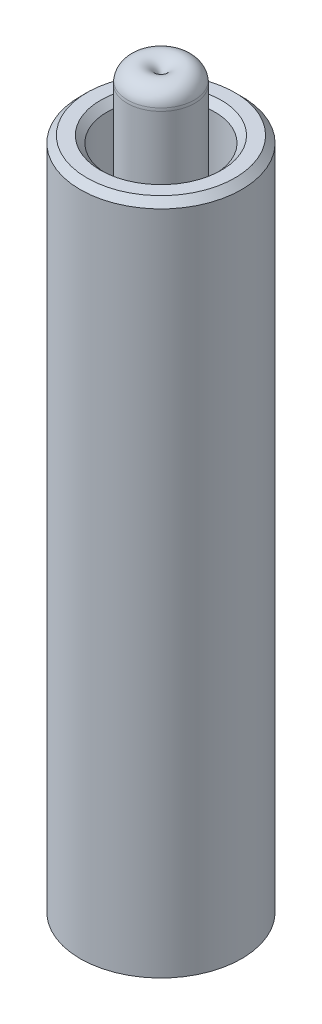
SolidWorks part; units mm, degrees
ref_plane "前视基准面" through (0, 0, 0) normal (0, 0, 1) x (1, 0, 0)
ref_plane "上视基准面" through (0, 0, 0) normal (0, 1, 0) x (1, 0, 0)
ref_plane "右视基准面" through (0, 0, 0) normal (1, 0, 0) x (0, 0, -1)
other "Configuration Table"
sketch "草图1" plane through (0, 0, 0) normal (0, 1, 0) x (1, 0, 0)
  circle A0 centre (0, 0) radius 6
  dimension "D1" = 12
extrude "凸台-拉伸1" add sketch "草图1" along normal blind 50
sketch "草图2" plane through (0, 50, 0) normal (0, 1, 0) x (1, 0, 0)
  circle A0 centre (0, 0) radius 4
  circle A1 centre (0, 0) radius 6 construction
  circle A2 centre (0, 0) radius 2.5
  dimension "D1" = 2
  dimension "D2" = 1.5
extrude "切除-拉伸1" cut sketch "草图2" against normal blind 8
sketch "草图3" plane through (0, 50, 0) normal (0, 1, 0) x (1, 0, 0)
  circle A0 centre (0, 0) radius 2.5
extrude "凸台-拉伸2" add sketch "草图3" along normal blind 5
fillet "圆角1" radius 1.7 1 edges at (0, 55, 2.5)
sketch "草图4" plane through (0, 55, 0) normal (0, 1, 0) x (1, 0, 0)
  circle A0 centre (0, 0) radius 0.0961
extrude "切除-拉伸2" cut sketch "草图4" against normal blind 5
fillet "圆角2" radius 1.2 1 edges at (0, 55, 0.0961)
chamfer "倒角1" distance 0.5 angle 45 2 edges at (0, 50, 6) (0, 50, 4)
